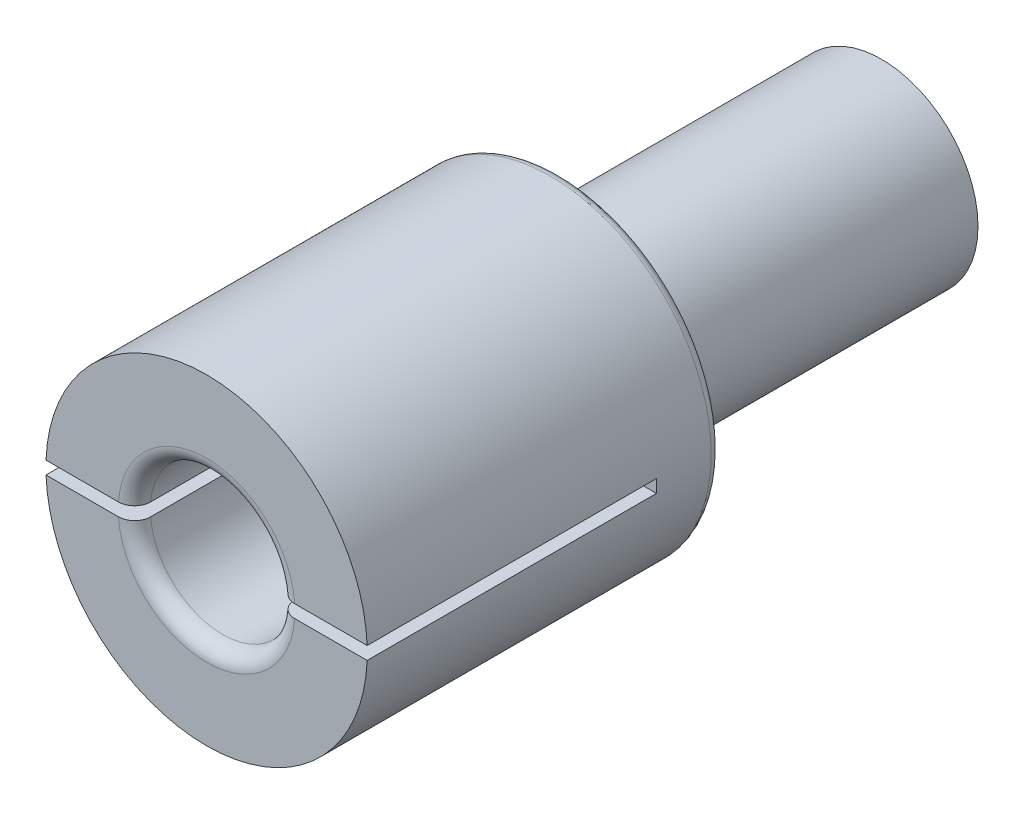
SolidWorks part; units mm, degrees
material "Cobre forjado"
ref_plane "Plano frontal" through (0, 0, 0) normal (0, 0, 1) x (1, 0, 0)
ref_plane "Plano superior" through (0, 0, 0) normal (0, 1, 0) x (1, 0, 0)
ref_plane "Plano direito" through (0, 0, 0) normal (1, 0, 0) x (0, 0, -1)
sketch "Esboço1" plane through (0, 0, 0) normal (0, 0, 1) x (1, 0, 0)
  circle A0 centre (-26.1833, 4.3838) radius 5
  dimension "D1" = 10
extrude "Ressalto-extrusão1" add sketch "Esboço1" along normal blind 11
sketch "Esboço2" plane through (0, 0, 11) normal (0, 0, 1) x (1, 0, 0)
  circle A0 centre (-26.1833, 4.3838) radius 2.25
  dimension "D1" = 4.5
extrude "Corte-extrusão1" cut sketch "Esboço2" against normal blind 11
sketch "Esboço3" plane through (0, 0, 0) normal (0, 0, -1) x (-1, 0, 0)
  circle A0 centre (26.1833, 4.3838) radius 3
  dimension "D1" = 6
extrude "Ressalto-extrusão2" add sketch "Esboço3" along normal blind 10
cosmetic thread "Representação de rosca1" parameters "D2"=4.891
sketch "Esboço4" plane through (0, 0, 11) normal (0, 0, 1) x (1, 0, 0)
  line L0 (-26.1833, 4.3838) -> (49973.8167, 4.3838) construction
  line L1 (-31.1833, 4.3838) -> (-21.1833, 4.3838) construction
  line L2 (-31.1833, 4.5838) -> (-21.1833, 4.5838)
  line L3 (-31.1833, 4.1838) -> (-21.1833, 4.1838)
  circle A0 centre (-26.1833, 4.3838) radius 5 construction
  arc A1 (-31.1833, 4.5838) -> (-31.1833, 4.1838) centre (-31.1833, 4.3838) ccw
  arc A2 (-21.1833, 4.1838) -> (-21.1833, 4.5838) centre (-21.1833, 4.3838) ccw
  point P7 (-26.1833, 4.3838)
  dimension "D1" = 0.4
extrude "Corte-extrusão2" cut sketch "Esboço4" against normal blind 9
fillet "Filete1" radius 0.5 2 edges at (-26.1833, 2.1338, 11) (-26.1833, 6.6338, 11)
fillet "Filete2" radius 0.3 1 edges at (-21.1833, 4.3838, 0)
